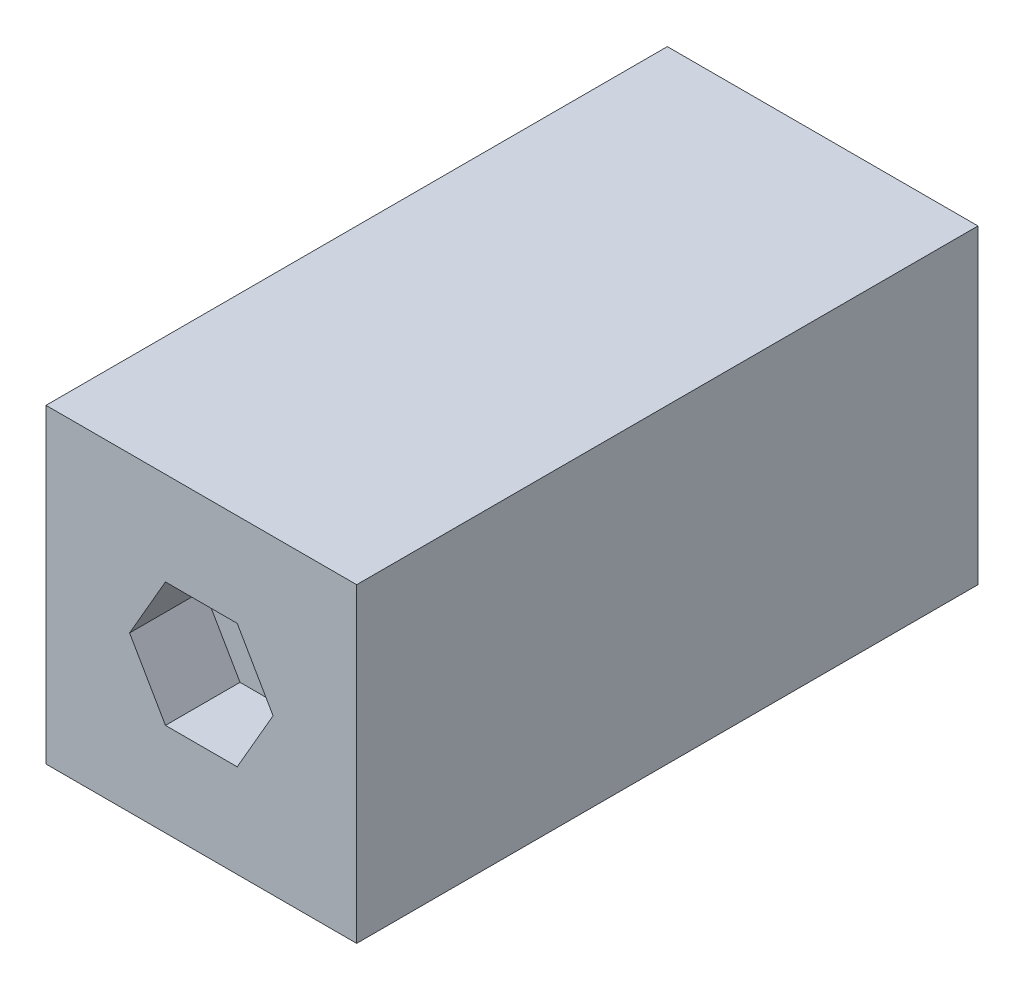
SolidWorks part; units mm, degrees
ref_plane "Alzado" through (0, 0, 0) normal (0, 0, 1) x (1, 0, 0)
ref_plane "Planta" through (0, 0, 0) normal (0, 1, 0) x (1, 0, 0)
ref_plane "Vista lateral" through (0, 0, 0) normal (1, 0, 0) x (0, 0, -1)
sketch "Croquis1" plane through (0, 0, 0) normal (0, 0, 1) x (1, 0, 0)
  line L1 (0, 0) -> (25, 0)
  line L2 (0, 0) -> (0, 25)
  line L3 (0, 25) -> (25, 25)
  line L4 (25, 0) -> (25, 25)
  dimension "D1" = 25
  dimension "D2" = 25
extrude "Saliente-Extruir1" add sketch "Croquis1" along normal blind 50
sketch "Croquis2" plane through (0, 0, 50) normal (0, 0, 1) x (1, 0, 0)
  line L1 (18.2735, 12.5) -> (15.3868, 17.5)
  line L2 (15.3868, 17.5) -> (9.6132, 17.5)
  line L3 (9.6132, 17.5) -> (6.7265, 12.5)
  line L4 (6.7265, 12.5) -> (9.6132, 7.5)
  line L5 (9.6132, 7.5) -> (15.3868, 7.5)
  line L6 (15.3868, 7.5) -> (18.2735, 12.5)
  circle A0 centre (12.5, 12.5) radius 5 construction
  dimension "D1" = 10
extrude "Cortar-Extruir1" cut sketch "Croquis2" against normal blind 6
